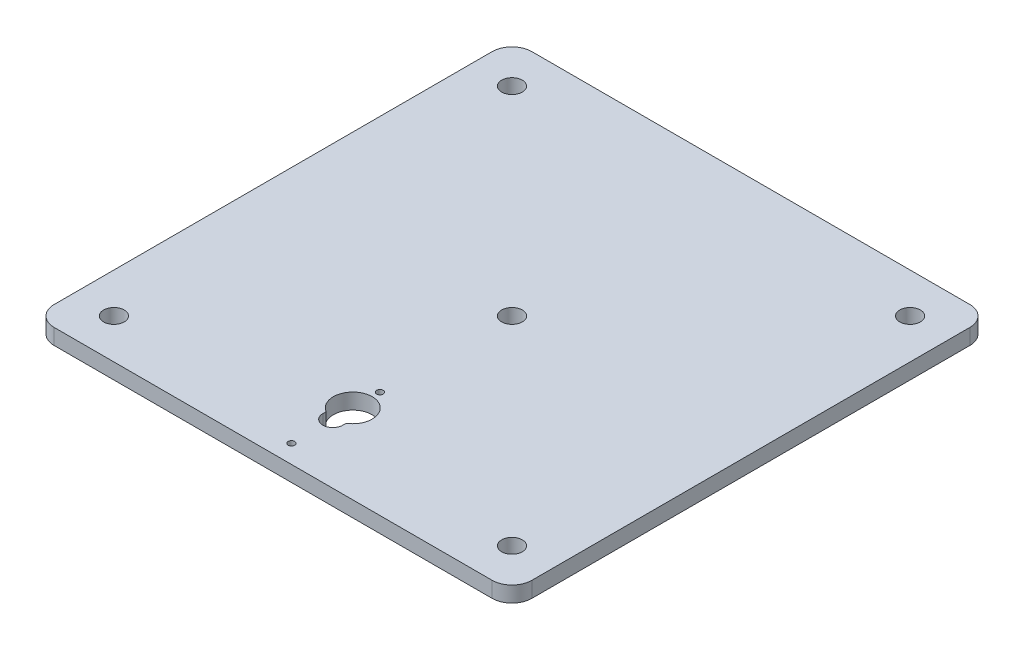
SolidWorks part; units mm, degrees
ref_plane "Front Plane" through (0, 0, 0) normal (0, 0, 1) x (1, 0, 0)
ref_plane "Top Plane" through (0, 0, 0) normal (0, 1, 0) x (1, 0, 0)
ref_plane "Right Plane" through (0, 0, 0) normal (1, 0, 0) x (0, 0, -1)
sketch "Sketch1" plane through (0, 0, 0) normal (0, 1, 0) x (1, 0, 0)
  line L0 (0, 76.2) -> (0, -76.2) construction
  line L1 (-69.85, 76.2) -> (69.85, 76.2)
  line L2 (-76.2, 69.85) -> (-76.2, -69.85)
  line L3 (-69.85, -76.2) -> (69.85, -76.2)
  line L4 (76.2, 69.85) -> (76.2, -69.85)
  line L5 (-76.2, 76.2) -> (76.2, -76.2) construction
  line L6 (-76.2, -76.2) -> (76.2, 76.2) construction
  line L7 (-76.2, 0) -> (76.2, 0) construction
  arc A0 (-76.2, -69.85) -> (-69.85, -76.2) centre (-69.85, -69.85) ccw
  arc A1 (69.85, -76.2) -> (76.2, -69.85) centre (69.85, -69.85) ccw
  arc A2 (69.85, 76.2) -> (76.2, 69.85) centre (69.85, 69.85) cw
  arc A3 (-69.85, 76.2) -> (-76.2, 69.85) centre (-69.85, 69.85) ccw
  circle A5 centre (63.5, 63.5) radius 3.302
  circle A6 centre (63.5, -63.5) radius 3.302
  circle A7 centre (-63.5, -63.5) radius 3.302
  circle A8 centre (-63.5, 63.5) radius 3.302
  circle A9 centre (0, 0) radius 3.302
  circle A10 centre (0, 0) radius 38.1 construction
  circle A11 centre (0, -50.8) radius 12.7 construction
  point P0 (0, 0)
  point P35 (0, 0)
  point P36 (0, -50.8)
  dimension "D3" = 6.35
  dimension "D4" = 12.7
  dimension "D5" = 6.604
  dimension "D7" = 6.604
  dimension "D8" = 76.2
  dimension "D9" = 25.4
  dimension "D1" = 152.4
  dimension "D2" = 152.4
  dimension "D6" = 12.7
sketch "Sketch2" plane through (0, 0, 0) normal (0, 1, 0) x (1, 0, 0)
  line L2 (0, 76.2) -> (0, -76.2) construction
  line L3 (-3.2, -56.1104) -> (-3.2, -57.15)
  line L4 (2.7, -55.82) -> (2.7, -57.15) construction
  line L5 (-2.7, -55.82) -> (-2.7, -57.15) construction
  line L6 (3.2, -56.1104) -> (3.2, -57.15)
  arc A13 (2.7, -55.82) -> (-2.7, -55.82) centre (0, -50.8) ccw construction
  arc A14 (-2.7, -57.15) -> (2.7, -57.15) centre (0, -57.15) ccw construction
  arc A15 (3.2, -56.1104) -> (-3.2, -56.1104) centre (0, -50.8) ccw
  arc A16 (-3.2, -57.15) -> (3.2, -57.15) centre (0, -57.15) ccw
  circle A17 centre (0, -42.125) radius 1.05
  circle A18 centre (0, -70.375) radius 1.05
  point P7 (0, -59.85)
  point P8 (0, -45.1)
  point P19 (0, -40.1698)
  point P22 (0, -66.7185)
  point P23 (0, 0)
  dimension "D1" = 11.4
  dimension "D2" = 5.4
  dimension "D4" = 2.7
  dimension "D8" = 28.25
  dimension "D9" = 8.675
  dimension "D7" = 2.1
  dimension "D3" = 14.75
  dimension "D5" = 2.7
  dimension "D6" = 0.5
extrude "Boss-Extrude1" add sketch "Sketch1" along normal blind 5
extrude "Cut-Extrude2" cut sketch "Sketch2" along normal through all
